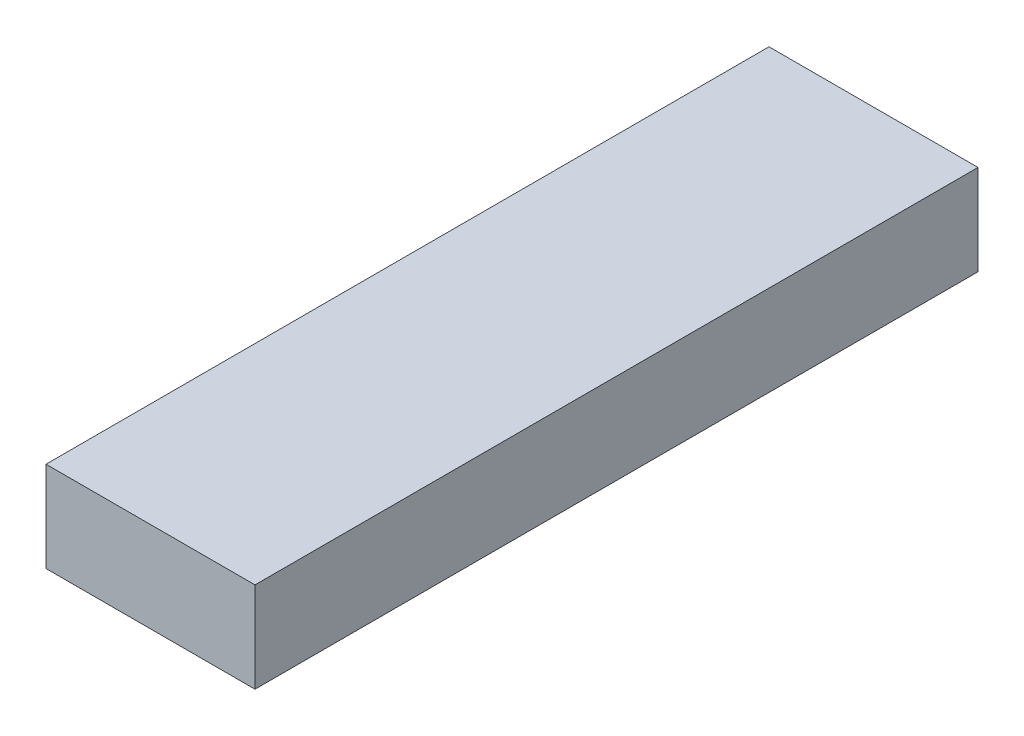
SolidWorks part; units mm, degrees
material "Pine"
ref_plane "Front Plane" through (0, 0, 0) normal (0, 0, 1) x (1, 0, 0)
ref_plane "Top Plane" through (0, 0, 0) normal (0, 1, 0) x (1, 0, 0)
ref_plane "Right Plane" through (0, 0, 0) normal (1, 0, 0) x (0, 0, -1)
sketch "Sketch1" plane through (0, 0, 0) normal (0, 0, 1) x (1, 0, 0)
  line L1 (44.0531, -19.05) -> (-44.0531, -19.05)
  line L2 (44.0531, -19.05) -> (44.0531, 19.05)
  line L3 (44.0531, 19.05) -> (-44.0531, 19.05)
  line L4 (-44.0531, -19.05) -> (-44.0531, 19.05)
  line L5 (44.0531, -19.05) -> (-44.0531, 19.05) construction
  line L6 (44.0531, 19.05) -> (-44.0531, -19.05) construction
  point P0 (0, 0)
  dimension "D1" = 88.1063
  dimension "D2" = 38.1
extrude "Boss-Extrude1" add sketch "Sketch1" along normal blind 304.8
